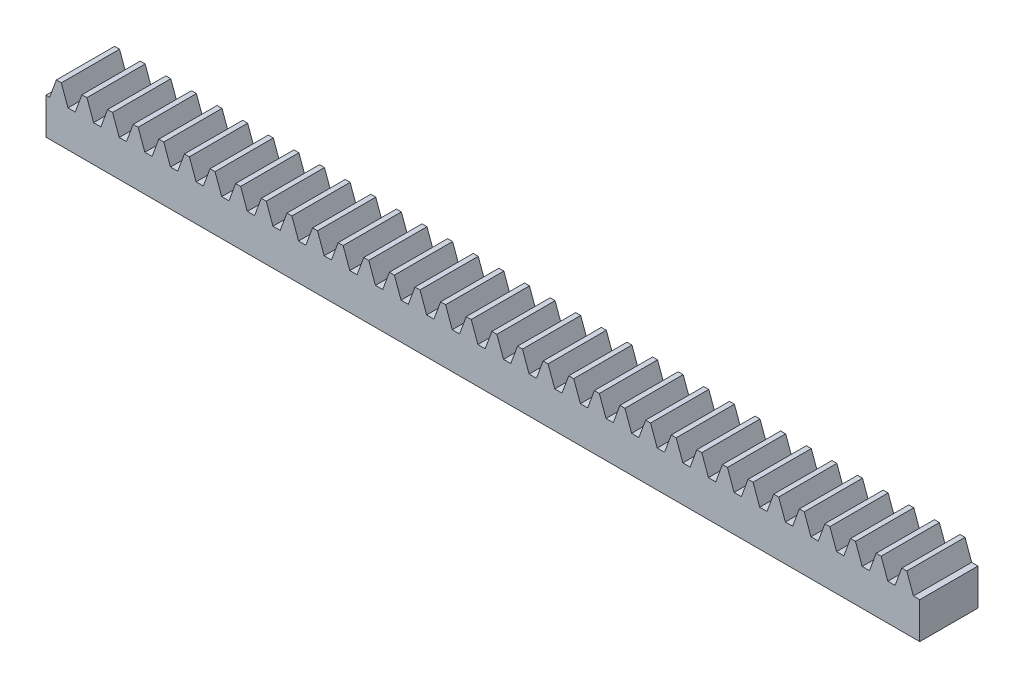
SolidWorks part; units mm, degrees
extrude "Blank" add sketch "BlankSke" against normal blind 5
sketch "BlankSke" plane through (0, 0, 0) normal (0, 0, 1) x (1, 0, 0)
  line L1 (0, 0) -> (75, 0)
  line L2 (0, 0) -> (0, 4.7)
  line L3 (0, 4.7) -> (75, 4.7)
  line L4 (75, 0) -> (75, 4.7)
  dimension "Length" = 75
  dimension "Blank_height" = 4.7
ref_plane "Plane1" through (0, 0, 0) normal (0, 0, 1) x (1, 0, 0)
ref_plane "Plane2" through (0, 0, 0) normal (0, 1, 0) x (1, 0, 0)
ref_plane "Plane3" through (0, 0, 0) normal (1, 0, 0) x (0, 0, -1)
other "Configuration Table"
sketch "HoldingSke" plane through (0, 0, 0) normal (0, 1, 0) x (1, 0, 0)
  line L0 (0, 0) -> (0.1988, 1.4147)
  line L1 (-15, 0) -> (100, 0) construction
  line L2 (0, 0) -> (-2.1039, 2.3779)
  line L3 (0, 0) -> (-11.863, 4.5341)
  line L4 (0, 0) -> (6.9867, 5.0761)
  line L5 (0, 0) -> (-23.7986, -8.8762)
  line L6 (0, 0) -> (-10.5278, -7.1032)
  line L9 (-71.009, 38.7566) -> (-0.532, 64.4081)
  line L10 (-76.2, 3.0779) -> (-72.2, 3.0779)
  line L11 (0, 0) -> (-5, 0)
  line L12 (-76.2, 101.6) -> (-76.173, 101.6)
  line L13 (24.9733, 27.94) -> (52.9518, 28.4284)
  line L14 (24.9733, 27.94) -> (24.9743, 27.94)
  line L15 (24.9733, 27.94) -> (100.4006, 29.5858)
  circle A0 centre (0, 0) radius 19.05
  circle A1 centre (0, 0) radius 2
  circle A2 centre (0, 0) radius 12.7
  dimension "MPH" = 4
  dimension "Diameter" = 38.1
  dimension "Num_teeth" = 36
  dimension "Pitch" = 1.4286
  dimension "Show_teeth" = 998
  dimension "Thickness" = 12.7
  dimension "Ap" = 20
  dimension "Pitch_height" = 4
  dimension "Width" = 5
  dimension "Backlash" = 0.027
  dimension "Addendum_fac" = 1
  dimension "Dedendum_fac" = 1.25
  dimension "Clearance_fac" = 0.25
  dimension "Dedendum_add" = 0.001
  dimension "Length" = 75
  dimension "Module" = 0.7
sketch "TooCutSkeIll" plane through (0, 0, 0) normal (0, 0, 1) x (1, 0, 0)
  line L0 (-0.8789, 4.6816) -> (-0.3545, 3.2408)
  line L1 (-0.1891, 3.125) -> (0.1891, 3.125)
  line L2 (0.3545, 3.2408) -> (0.8789, 4.6816)
  line L3 (75, 4.7) -> (0, 4.7) construction
  line L4 (0, 0) -> (0, 64.897) construction
  line L5 (-13.208, 4) -> (12.954, 4) construction
  line L6 (0, 0) -> (75, 0) construction
  line L7 (0.6308, 4) -> (0.6308, 48.7463) construction
  line L8 (-0.6308, 4) -> (-0.6308, 48.7463) construction
  line L9 (0.9052, 4.7) -> (0.9052, 4.7254)
  line L10 (-0.9052, 4.7) -> (-0.9052, 4.7254)
  line L11 (-0.9052, 4.7254) -> (0.9052, 4.7254)
  arc A0 (0.1891, 3.125) -> (0.3545, 3.2408) centre (0.1891, 3.301) ccw
  arc A1 (-0.3545, 3.2408) -> (-0.1891, 3.125) centre (-0.1891, 3.301) ccw
  arc A2 (0.9052, 4.7) -> (0.8789, 4.6816) centre (0.9052, 4.672) ccw
  arc A3 (-0.8789, 4.6816) -> (-0.9052, 4.7) centre (-0.9052, 4.672) ccw
  dimension "Pitch_height" = 4
  dimension "Addendum_plus" = 0.7254
  dimension "Pressure_angle" = 20
  dimension "Gap_width" = 1.2616
  dimension "Dedendum" = 0.875
extrude "ToothCutIll" [suppressed] cut sketch "TooCutSkeIll" against normal through all
sketch "TooCutSkeSim" plane through (0, 0, 0) normal (0, 0, 1) x (1, 0, 0)
  line L0 (0.3123, 3.125) -> (-0.3123, 3.125)
  line L1 (0.8948, 4.7254) -> (0.3123, 3.125)
  line L2 (0, 17.4625) -> (0, 53.467) construction
  line L3 (0.8948, 4.7254) -> (-0.8948, 4.7254)
  line L6 (-0.8948, 4.7254) -> (-0.3123, 3.125)
  line L9 (-0.6308, 4) -> (0.6308, 4) construction
  line L10 (0, 0) -> (75, 0) construction
  line L11 (0.6308, 4) -> (0.6308, 53.467) construction
  line L12 (-0.6308, 4) -> (-0.6308, 53.467) construction
  dimension "Pitch_height" = 4
  dimension "Addendum_plus" = 0.7254
  dimension "Pressure_angle" = 20
  dimension "Gap_width" = 1.2616
  dimension "Dedendum" = 0.875
extrude "ToothCutSim" cut sketch "TooCutSkeSim" against normal through all
pattern_linear "TeethCuts" count 35 spacing 2.1991 along (1, 0, 0) of "ToothCutIll", "ToothCutSim"
equation "' \"Module@HoldingSke\" = 6.35"
equation "' \"Num_teeth@HoldingSke\" = 12"
equation "' \"Ap@HoldingSke\" =  20"
equation "' \"Ap@HoldingSke\" = 20"
equation "' \"Width@HoldingSke\" = 0.25 * 25.4"
equation "' \"Show_teeth@HoldingSke\" = 500"
equation "' \"Backlash@HoldingSke\" = 0.009 * 25.4"
equation "' \"Addendum_fac@HoldingSke\" = 1.0"
equation "' \"Dedendum_fac@HoldingSke\" = 1.25"
equation "' \"Dedendum_add@HoldingSke\" = 0.00005 * 25.4"
equation "' \"Clearance_fac@HoldingSke\" = 0.25"
equation "' \"Pitch_height@HoldingSke\" = 1 * 25.4"
equation "' \"Length@HoldingSke\" = 4.71 * 25.4"
equation "\"Pitch@HoldingSke\" = 1 / \"Module@HoldingSke\""
equation "\"MPH@HoldingSke\" = \"Dedendum_fac@HoldingSke\" / \"Pitch@HoldingSke\" + 2 * \"Dedendum_add@HoldingSke\" + 0.002 * 25.4"
equation "\"MPH@HoldingSke\" = ((sgn( \"MPH@HoldingSke\" - \"Pitch_height@HoldingSke\")+1)*( \"MPH@HoldingSke\" - \"Pitch_height@HoldingSke\"))/2 + \"Pitch_height@HoldingSke\""
equation "\"Blank_height@BlankSke\" = \"Pitch_height@HoldingSke\" + \"Addendum_fac@HoldingSke\"  / \"Pitch@HoldingSke\" "
equation "\"Length@BlankSke\" =  \"Length@HoldingSke\""
equation "\"Face_width@Blank\" = \"Width@HoldingSke\""
equation "\"Pressure_angle@TooCutSkeIll\" = \"Ap@HoldingSke\""
equation "\"Addendum_plus@TooCutSkeIll\" =  \"Addendum_fac@HoldingSke\"  / \"Pitch@HoldingSke\" + 0.001 *25.4"
equation "\"Dedendum@TooCutSkeIll\" = \"Dedendum_fac@HoldingSke\"  / \"Pitch@HoldingSke\""
equation "\"Pitch_height@TooCutSkeIll\" =  \"MPH@HoldingSke\""
equation "\"Gap_width@TooCutSkeIll\" = 3.14159265 / 2 / \"Pitch@HoldingSke\" + 6 * \"Backlash@HoldingSke\""
equation "\"Pressure_angle@TooCutSkeSim\" = \"Ap@HoldingSke\""
equation "\"Addendum_plus@TooCutSkeSim\" =  \"Addendum_fac@HoldingSke\"  / \"Pitch@HoldingSke\" + 0.001 * 25.4"
equation "\"Dedendum@TooCutSkeSim\" = \"Dedendum_fac@HoldingSke\"  / \"Pitch@HoldingSke\""
equation "\"Pitch_height@TooCutSkeSim\" =  \"MPH@HoldingSke\""
equation "\"Gap_width@TooCutSkeSim\" = 3.14159265 / 2 / \"Pitch@HoldingSke\" + 6 * \"Backlash@HoldingSke\""
equation "\"Root_fillet@TooCutSkeIll\" = \"Clearance_fac@HoldingSke\" / \"Pitch@HoldingSke\" + \"Dedendum_add@HoldingSke\""
equation "\"Break_rad@TooCutSkeIll\" = 0.02 / \"Pitch@HoldingSke\" * 2"
equation "\"Linear_pitch@TeethCuts\" = 3.14159265 / \"Pitch@HoldingSke\""
equation "\"Num_teeth@HoldingSke\" = int( ( \"Length@HoldingSke\" + 0 ) / (3.14159265 / \"Pitch@HoldingSke\")) + 0.9999  + 1"
equation " \"Num_teeth@TeethCuts\" = int( \"Show_teeth@HoldingSke\" ) + 1"
equation " \"Num_teeth@TeethCuts\" = ((sgn( \"Num_teeth@TeethCuts\" - \"Num_teeth@HoldingSke\" )-1)*( \"Num_teeth@TeethCuts\" - \"Num_teeth@HoldingSke\" ))/-2+ \"Num_teeth@HoldingSke\""
equation " \"Num_teeth@TeethCuts\" = ((sgn( \"Num_teeth@TeethCuts\" - 2.0)+1)*( \"Num_teeth@TeethCuts\" - 2.0))/2 +2.0"
